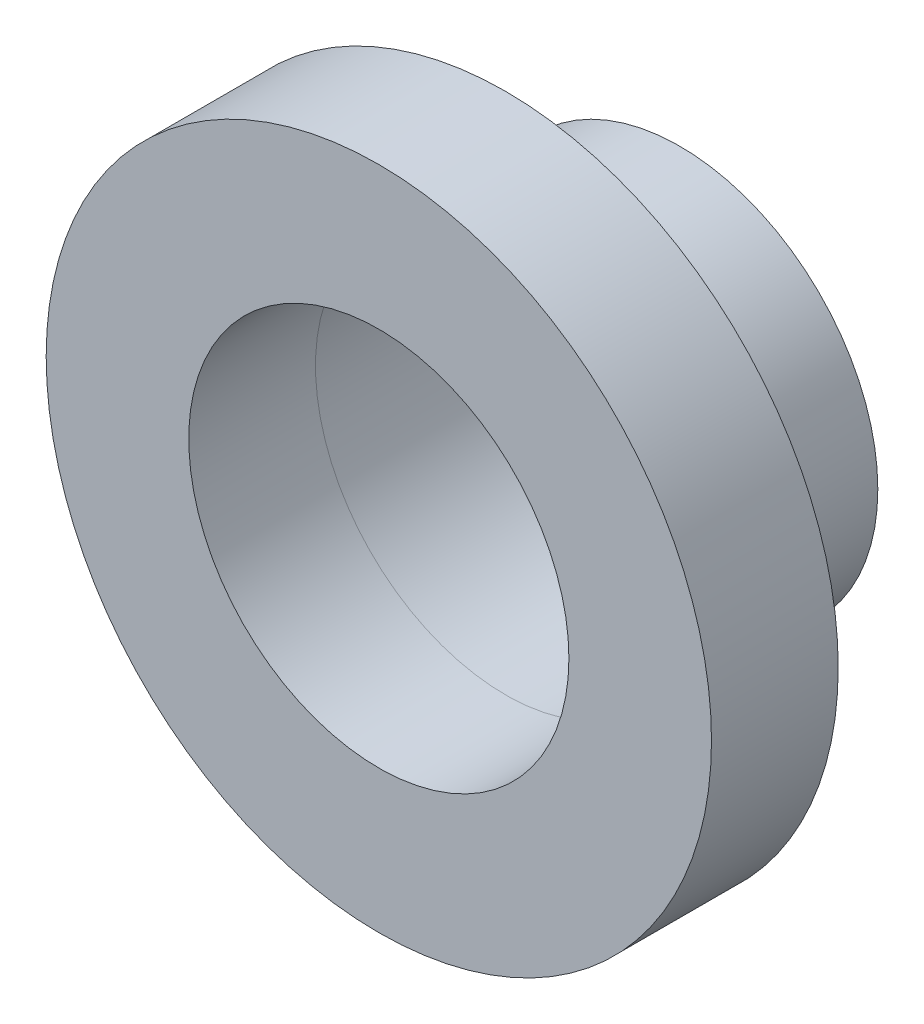
SolidWorks part; units mm, degrees
ref_plane "前视基准面" through (0, 0, 0) normal (0, 0, 1) x (1, 0, 0)
ref_plane "上视基准面" through (0, 0, 0) normal (0, 1, 0) x (1, 0, 0)
ref_plane "右视基准面" through (0, 0, 0) normal (1, 0, 0) x (0, 0, -1)
sketch "草图2" plane through (0, 0, 0) normal (0, 0, 1) x (1, 0, 0)
  circle A0 centre (0, 0) radius 12
  circle A1 centre (0, 0) radius 12.5
extrude "凸台-拉伸1" add sketch "草图2" along normal blind 11
sketch "草图3" plane through (0, 0, 11) normal (0, 0, 1) x (1, 0, 0)
  circle A0 centre (0, 0) radius 12
  circle A1 centre (0, 0) radius 21
extrude "凸台-拉伸2" add sketch "草图3" along normal blind 8 separate body
